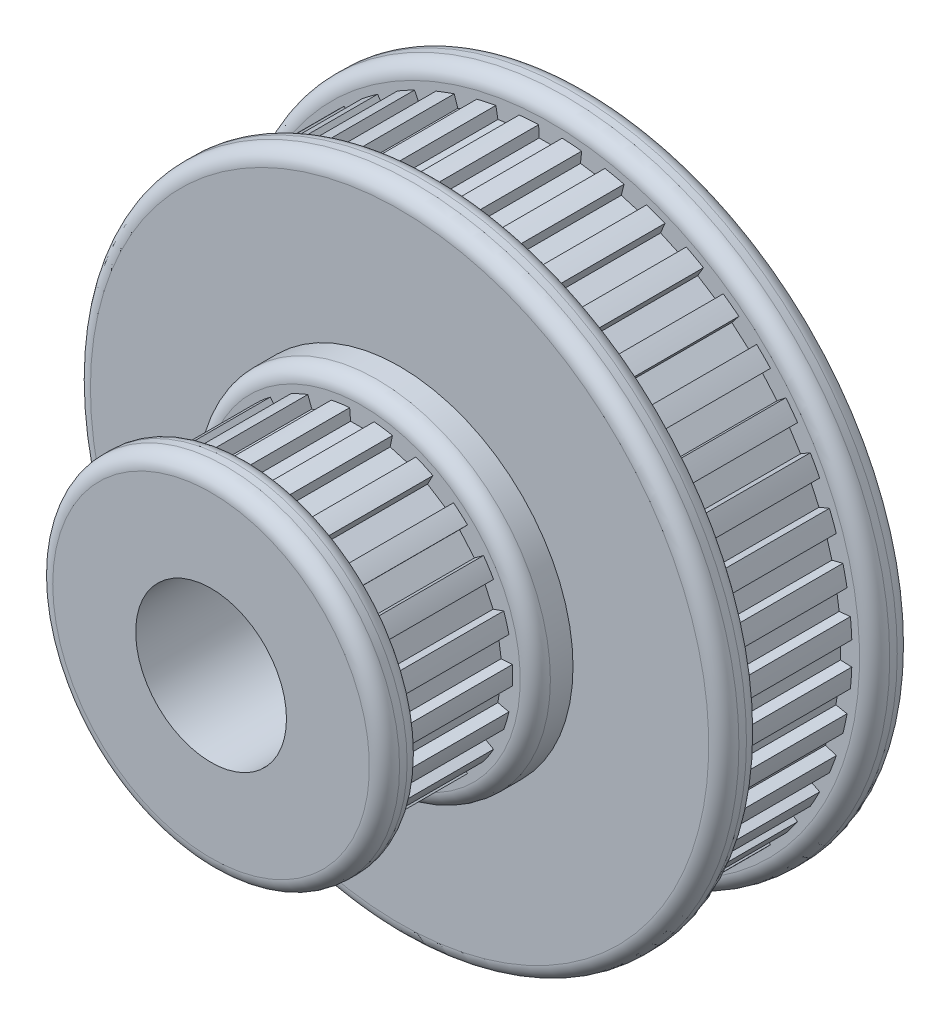
SolidWorks part; units mm, degrees
material "Teak"
ref_plane "Plano frontal" through (0, 0, 0) normal (0, 0, 1) x (1, 0, 0)
ref_plane "Plano superior" through (0, 0, 0) normal (0, 1, 0) x (1, 0, 0)
ref_plane "Plano direito" through (0, 0, 0) normal (1, 0, 0) x (0, 0, -1)
sketch "Sketch1" plane through (0, 0, 0) normal (1, 0, 0) x (0, 0, -1)
  line L0 (0, 0) -> (47.1541, 0) construction
  line L1 (0, 10) -> (50, 10)
  line L2 (50, 10) -> (50, 43)
  line L3 (50, 43) -> (45, 43)
  line L4 (45, 43) -> (45, 40)
  line L5 (45, 40) -> (30, 40)
  line L6 (30, 40) -> (30, 43)
  line L7 (30, 43) -> (25, 43)
  line L8 (25, 43) -> (25, 23)
  line L9 (25, 23) -> (20, 23)
  line L10 (20, 23) -> (20, 20)
  line L11 (20, 20) -> (5, 20)
  line L12 (5, 20) -> (5, 23)
  line L13 (5, 23) -> (0, 23)
  line L14 (0, 23) -> (0, 10)
  dimension "D1" = 5
  dimension "D2" = 15
  dimension "D3" = 5
  dimension "D4" = 5
  dimension "D5" = 5
  dimension "D6" = 15
  dimension "D7" = 43
  dimension "D8" = 3
  dimension "D9" = 23
  dimension "D10" = 10
  dimension "D11" = 3
revolve "Revolve1" add sketch "Sketch1" angle 360 about L0
sketch "Sketch2" plane through (0, 0, -20) normal (0, 0, 1) x (1, 0, 0)
  line L1 (-1.5, 18.4391) -> (1.5, 18.4391)
  line L2 (1.5, 18.4391) -> (1.6216, 19.9342)
  line L3 (-1.5, 18.4391) -> (-1.6216, 19.9342)
  circle A0 centre (0, 0) radius 20 construction
  arc A1 (1.6216, 19.9342) -> (-1.6216, 19.9342) centre (0, 0) ccw
  point P6 (0, 18.4391)
  dimension "D1" = 1.5
  dimension "D2" = 3
extrude "Cut-Extrude1" cut sketch "Sketch2" along normal up to surface (15 mm away) up to face at (23, 0, -5)
pattern_circular "CirPattern1" count 22 over 360 about axis through (0, 0, 0) along (0, 0, 1) of "Cut-Extrude1"
sketch "Sketch3" plane through (0, 0, -45) normal (0, 0, 1) x (1, 0, 0)
  line L0 (0, 0) -> (0, 38.4708) construction
  line L1 (-1.5, 38.4708) -> (1.5, 38.4708)
  line L2 (1.5, 38.4708) -> (1.5584, 39.9696)
  line L3 (-1.5, 38.4708) -> (-1.5584, 39.9696)
  circle A0 centre (0, 0) radius 40 construction
  arc A1 (1.5584, 39.9696) -> (-1.5584, 39.9696) centre (0, 0) ccw
  point P7 (0, 38.4708)
  dimension "D1" = 1.5
  dimension "D2" = 3
extrude "Cut-Extrude2" cut sketch "Sketch3" along normal up to surface (15 mm away) up to face at (43, 0, -30)
pattern_circular "CirPattern2" count 44 over 360 about axis through (0, 0, 0) along (0, 0, 1) of "Cut-Extrude2"
sketch "Sketch4" plane through (0, 0, 0) normal (1, 0, 0) x (0, 0, -1)
  line L0 (0, 0) -> (78.8889, 0) construction
  line L1 (0, 23) -> (0, -23) construction
  line L2 (50, 35.5) -> (40, 29.7265)
  line L3 (50, -43) -> (50, 43) construction
  line L4 (40, 29.7265) -> (40, 26.7735)
  line L5 (40, 26.7735) -> (50, 21)
  line L6 (50, 35.5) -> (50, 21)
  dimension "D1" = 7.5
  dimension "D2" = 14.5
  dimension "D3" = 60
  dimension "D4" = 10
revolve "Cut-Revolve1" cut sketch "Sketch4" angle 360 about L0
fillet "Fillet1" radius 2 11 edges at (23, 0, 0) (23, 0, -5) (23, 0, -20) (43, 0, -25) (43, 0, -30) (43, 0, -45) (43, 0, -50) (21, 0, -50) (35.5, 0, -50) (29.7265, 0, -40) (26.7735, 0, -40)
